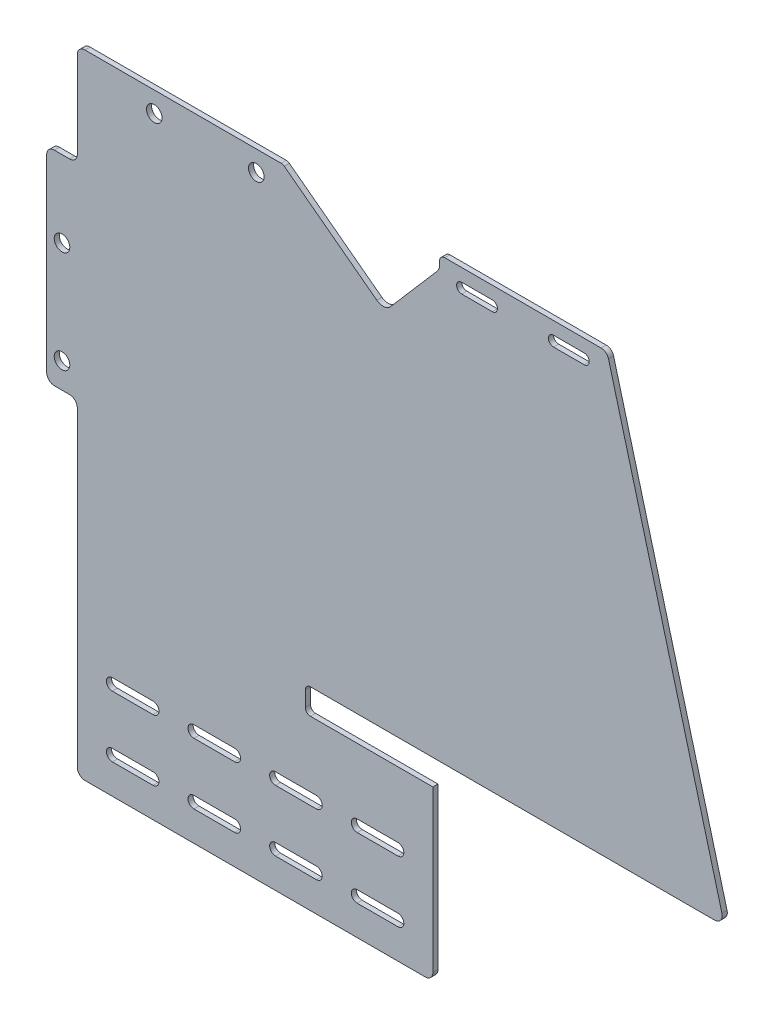
SolidWorks part; units mm, degrees
material "Thornel Mat VMA"
ref_plane "前视基准面" through (0, 0, 0) normal (0, 0, 1) x (1, 0, 0)
ref_plane "上视基准面" through (0, 0, 0) normal (0, 1, 0) x (1, 0, 0)
ref_plane "右视基准面" through (0, 0, 0) normal (1, 0, 0) x (0, 0, -1)
other "Configuration Table"
sketch "草图1" plane through (0, 0, 0) normal (0, 0, 1) x (1, 0, 0)
  line L1 (-70, -62) -> (70, -62)
  line L2 (-70, -62) -> (-70, 62)
  line L3 (-70, 62) -> (70, 62)
  line L4 (70, -62) -> (70, 62)
  line L5 (-70, -62) -> (70, 62) construction
  line L6 (-70, 62) -> (70, -62) construction
  point P0 (0, 0)
  dimension "D1" = 140
  dimension "D2" = 124
extrude "凸台-拉伸1" add sketch "草图1" along normal mid plane 1
sketch "草图2" plane through (0, 0, 0.5) normal (0, 0, 1) x (1, 0, 0)
  line L0 (59.9835, -33.7244) -> (46.4361, 16.8352) construction
  line L1 (59.9835, -33.7244) -> (46.4361, 16.8352) construction
  line L2 (3.7, -29) -> (49.7, -29) construction
  line L3 (1.7, -34.5) -> (1.7, -47.5) construction
  line L4 (3.7, -29) -> (49.7, -29) construction
  line L5 (1.7, -34.5) -> (1.7, -47.5) construction
  line L6 (-0.3, -62) -> (-0.3, -24)
  line L7 (-70, -62) -> (70, -62) construction
  line L8 (-0.3, -24) -> (56.8603, -24)
  line L9 (56.8603, -24) -> (33.8166, 62)
  line L10 (70, 62) -> (-70, 62) construction
  line L11 (33.8166, 62) -> (70, 62)
  line L12 (70, 62) -> (70, -62)
  line L13 (70, -62) -> (-0.3, -62)
  dimension "D1" = 1
  dimension "D2" = 5
  dimension "D3" = 2
extrude "切除-拉伸1" cut sketch "草图2" against normal mid plane 3
sketch "草图3" plane through (0, 0, 0.5) normal (0, 0, 1) x (1, 0, 0)
  line L0 (-70, 62) -> (-70, -62) construction
  line L1 (-76, 2) -> (-64, 2)
  line L2 (-76, 2) -> (-76, 42)
  line L3 (-76, 42) -> (-64, 42)
  line L4 (-64, 2) -> (-64, 42)
  line L5 (-76, 2) -> (-64, 42) construction
  line L6 (-76, 42) -> (-64, 2) construction
  line L7 (33.8166, 62) -> (-70, 62) construction
  point P0 (-70, 22)
  dimension "D1" = 40
  dimension "D2" = 20
  dimension "D3" = 6
extrude "凸台-拉伸2" add sketch "草图3" against normal up to surface (1 mm away) up to face at (-8.3205, -8, -0.5)
sketch "草图4" plane through (0, 0, -0.5) normal (0, 0, -1) x (-1, 0, 0)
  circle A0 centre (51, 58) radius 1.25 construction
  circle A1 centre (31, 58) radius 1.25 construction
  circle A2 centre (51, 58) radius 1.25 construction
  circle A3 centre (31, 58) radius 1.25 construction
  circle A4 centre (51, 58) radius 1.525
  circle A5 centre (31, 58) radius 1.525
  dimension "D1" = 3.05
extrude "切除-拉伸2" [suppressed] cut sketch "草图4" against normal blind 10
sketch "草图5" plane through (0, 0, -0.5) normal (0, 0, -1) x (-1, 0, 0)
  circle A0 centre (34.9154, 58) radius 1.25 construction
  circle A1 centre (54.9154, 58) radius 1.25 construction
  circle A2 centre (34.9154, 58) radius 1.25 construction
  circle A3 centre (54.9154, 58) radius 1.25 construction
  circle A4 centre (73, 7) radius 1.25 construction
  circle A5 centre (73, 27) radius 1.25 construction
  circle A6 centre (73, 7) radius 1.25 construction
  circle A7 centre (73, 27) radius 1.25 construction
  circle A8 centre (34.9154, 58) radius 1.525
  circle A9 centre (54.9154, 58) radius 1.525
  circle A10 centre (73, 27) radius 1.525
  circle A11 centre (73, 7) radius 1.525
  dimension "D1" = 3.05
extrude "切除-拉伸3" cut sketch "草图5" against normal blind 10
sketch "草图6" [suppressed] plane through (0, 0, 0.5) normal (0, 0, 1) x (1, 0, 0)
  circle A0 centre (-73.0846, 7) radius 1.25 construction
  circle A1 centre (-73.0846, 27) radius 1.25 construction
  circle A2 centre (-73.0846, 7) radius 1.25 construction
  circle A3 centre (-73.0846, 27) radius 1.25 construction
  circle A4 centre (-73.0846, 27) radius 1.525
  circle A5 centre (-73.0846, 7) radius 1.525
  dimension "D1" = 3.05
extrude "切除-拉伸4" [suppressed] cut sketch "草图6" against normal blind 10
fillet "圆角1" radius 1.5 10 edges at (-70, -62, 0) (-0.3, -62, 0) (-0.3, -24, 0) (56.8603, -24, 0) (33.8166, 62, 0) (-70, 62, 0) (-76, 2, 0) (-70, 2, 0) (-70, 42, 0) (-76, 42, 0)
sketch "草图8" plane through (0, 0, -0.5) normal (0, 0, -1) x (-1, 0, 0)
  line L0 (0.3, -60.5) -> (0.3, -25.5) construction
  line L1 (-1.2, -24) -> (25.3, -24)
  line L2 (-1.2, -24) -> (-1.2, -29)
  line L3 (-1.2, -29) -> (25.3, -29)
  line L4 (25.3, -24) -> (25.3, -29)
  dimension "D1" = 5
  dimension "D2" = 25
extrude "切除-拉伸5" cut sketch "草图8" against normal blind 10
sketch "草图9" plane through (0, 0, -0.5) normal (0, 0, -1) x (-1, 0, 0)
  line L0 (351.7846, -49) -> (-51.6154, -49) construction
  line L1 (70, -49) -> (0.3, -49) construction
  line L2 (23.15, -43) -> (31.15, -43) construction
  line L3 (23.15, -41.85) -> (31.15, -41.85)
  line L4 (23.15, -44.15) -> (31.15, -44.15)
  line L5 (0.3, -60.5) -> (0.3, -29) construction
  line L6 (70, 0.5) -> (70, -60.5) construction
  line L7 (35.15, -58.9055) -> (35.15, -39.0945) construction
  line L8 (7.15, -43) -> (15.15, -43) construction
  line L9 (7.15, -41.85) -> (15.15, -41.85)
  line L10 (7.15, -44.15) -> (15.15, -44.15)
  line L11 (47.15, -43) -> (39.15, -43) construction
  line L12 (47.15, -41.85) -> (39.15, -41.85)
  line L13 (47.15, -44.15) -> (39.15, -44.15)
  line L14 (63.15, -43) -> (55.15, -43) construction
  line L15 (63.15, -41.85) -> (55.15, -41.85)
  line L16 (63.15, -44.15) -> (55.15, -44.15)
  line L17 (23.15, -55) -> (31.15, -55) construction
  line L18 (23.15, -56.15) -> (31.15, -56.15)
  line L19 (23.15, -53.85) -> (31.15, -53.85)
  line L20 (7.15, -55) -> (15.15, -55) construction
  line L21 (7.15, -56.15) -> (15.15, -56.15)
  line L22 (7.15, -53.85) -> (15.15, -53.85)
  line L23 (47.15, -55) -> (39.15, -55) construction
  line L24 (47.15, -56.15) -> (39.15, -56.15)
  line L25 (47.15, -53.85) -> (39.15, -53.85)
  line L26 (63.15, -55) -> (55.15, -55) construction
  line L27 (63.15, -56.15) -> (55.15, -56.15)
  line L28 (63.15, -53.85) -> (55.15, -53.85)
  arc A0 (23.15, -41.85) -> (23.15, -44.15) centre (23.15, -43) ccw
  arc A1 (31.15, -44.15) -> (31.15, -41.85) centre (31.15, -43) ccw
  arc A2 (7.15, -41.85) -> (7.15, -44.15) centre (7.15, -43) ccw
  arc A3 (15.15, -44.15) -> (15.15, -41.85) centre (15.15, -43) ccw
  arc A4 (47.15, -41.85) -> (47.15, -44.15) centre (47.15, -43) cw
  arc A5 (39.15, -44.15) -> (39.15, -41.85) centre (39.15, -43) cw
  arc A6 (63.15, -41.85) -> (63.15, -44.15) centre (63.15, -43) cw
  arc A7 (55.15, -44.15) -> (55.15, -41.85) centre (55.15, -43) cw
  arc A8 (23.15, -56.15) -> (23.15, -53.85) centre (23.15, -55) cw
  arc A9 (31.15, -53.85) -> (31.15, -56.15) centre (31.15, -55) cw
  arc A10 (7.15, -56.15) -> (7.15, -53.85) centre (7.15, -55) cw
  arc A11 (15.15, -53.85) -> (15.15, -56.15) centre (15.15, -55) cw
  arc A12 (47.15, -56.15) -> (47.15, -53.85) centre (47.15, -55) ccw
  arc A13 (39.15, -53.85) -> (39.15, -56.15) centre (39.15, -55) ccw
  arc A14 (63.15, -56.15) -> (63.15, -53.85) centre (63.15, -55) ccw
  arc A15 (55.15, -53.85) -> (55.15, -56.15) centre (55.15, -55) ccw
  point P4 (27.15, -43)
  point P20 (11.15, -43)
  point P26 (43.15, -43)
  point P33 (59.15, -43)
  point P40 (27.15, -55)
  point P47 (11.15, -55)
  point P54 (43.15, -55)
  point P61 (59.15, -55)
  point P67 (35.15, -49)
  dimension "D1" = 1.15
  dimension "D2" = 6
  dimension "D3" = 4
  dimension "D4" = 8
  dimension "D6" = 8
  dimension "D5" = 2
extrude "切除-拉伸6" cut sketch "草图9" against normal blind 10
sketch "草图10" plane through (0, 0, 0.5) normal (0, 0, 1) x (1, 0, 0)
  line L0 (-17.6593, 55.428) -> (-29.6389, 64.4553) construction
  line L1 (-17.6593, 55.428) -> (-29.6389, 64.4553) construction
  line L2 (1.0211, 61) -> (1.0211, 62) construction
  line L3 (1.0211, 59.5312) -> (1.0211, 62)
  line L4 (-29.7039, 62) -> (-9.7982, 47)
  line L5 (32.6656, 62) -> (-68.5, 62) construction
  line L6 (-9.7982, 47) -> (1.0211, 59.5312)
  line L7 (-29.7039, 62) -> (1.0211, 62)
  dimension "D1" = 2
  dimension "D2" = 15
  dimension "D3" = 2.4688
extrude "切除-拉伸7" cut sketch "草图10" against normal blind 10
fillet "圆角2" radius 2 2 edges at (1.0211, 59.5312, 0) (-9.7982, 47, 0)
fillet "圆角3" radius 1 2 edges at (1.0211, 62, 0) (-29.7039, 62, 0)
fillet "圆角4" radius 1 2 edges at (-25.3, -24, 0) (-25.3, -29, 0)
sketch "草图11" plane through (0, 0, -0.5) normal (0, 0, -1) x (-1, 0, 0)
  line L0 (-17.3433, 62) -> (-17.3433, 58.4642) construction
  line L1 (-32.6656, 62) -> (-2.0211, 62) construction
  line L2 (-29.3433, 58.5) -> (-23.3433, 58.5) construction
  line L3 (-29.3433, 59.5) -> (-23.3433, 59.5)
  line L4 (-29.3433, 57.5) -> (-23.3433, 57.5)
  line L5 (-5.3433, 58.5) -> (-11.3433, 58.5) construction
  line L6 (-5.3433, 59.5) -> (-11.3433, 59.5)
  line L7 (-5.3433, 57.5) -> (-11.3433, 57.5)
  arc A0 (-29.3433, 59.5) -> (-29.3433, 57.5) centre (-29.3433, 58.5) ccw
  arc A1 (-23.3433, 57.5) -> (-23.3433, 59.5) centre (-23.3433, 58.5) ccw
  arc A2 (-5.3433, 59.5) -> (-5.3433, 57.5) centre (-5.3433, 58.5) cw
  arc A3 (-11.3433, 57.5) -> (-11.3433, 59.5) centre (-11.3433, 58.5) cw
  point P6 (-26.3433, 58.5)
  point P13 (-8.3433, 58.5)
  dimension "D1" = 2
  dimension "D2" = 6
  dimension "D3" = 6
  dimension "D4" = 2.5
extrude "切除-拉伸8" cut sketch "草图11" against normal mid plane 10
